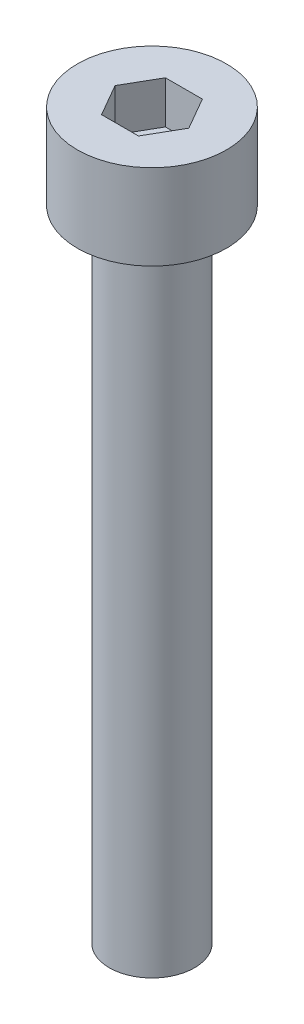
SolidWorks part; units mm, degrees
ref_plane "Front Plane" through (0, 0, 0) normal (0, 0, 1) x (1, 0, 0)
ref_plane "Top Plane" through (0, 0, 0) normal (0, 1, 0) x (1, 0, 0)
ref_plane "Right Plane" through (0, 0, 0) normal (1, 0, 0) x (0, 0, -1)
sketch "Sketch1" plane through (0, 0, 0) normal (0, 0, 1) x (1, 0, 0)
  line L0 (0, 0) -> (0, -30)
  line L1 (0, -30) -> (2, -30)
  line L2 (2, -30) -> (2, 0)
  line L3 (2, 0) -> (3.5, 0)
  line L4 (3.5, 0) -> (3.5, 4)
  line L5 (0, 0) -> (0, 4)
  line L6 (0, 4) -> (3.5, 4)
  dimension "D1" = 30
  dimension "D2" = 2
  dimension "D3" = 4
  dimension "D4" = 3.5
revolve "Revolve1" add sketch "Sketch1" angle 360 about L0
sketch "Sketch2" plane through (0, 4, 0) normal (0, 1, 0) x (1, 0, 0)
  line L1 (1.7321, 0) -> (0.866, 1.5)
  line L2 (0.866, 1.5) -> (-0.866, 1.5)
  line L3 (-0.866, 1.5) -> (-1.7321, 0)
  line L4 (-1.7321, 0) -> (-0.866, -1.5)
  line L5 (-0.866, -1.5) -> (0.866, -1.5)
  line L6 (0.866, -1.5) -> (1.7321, 0)
  circle A0 centre (0, 0) radius 1.5 construction
  dimension "D1" = 3
extrude "Cut-Extrude1" cut sketch "Sketch2" against normal blind 2
